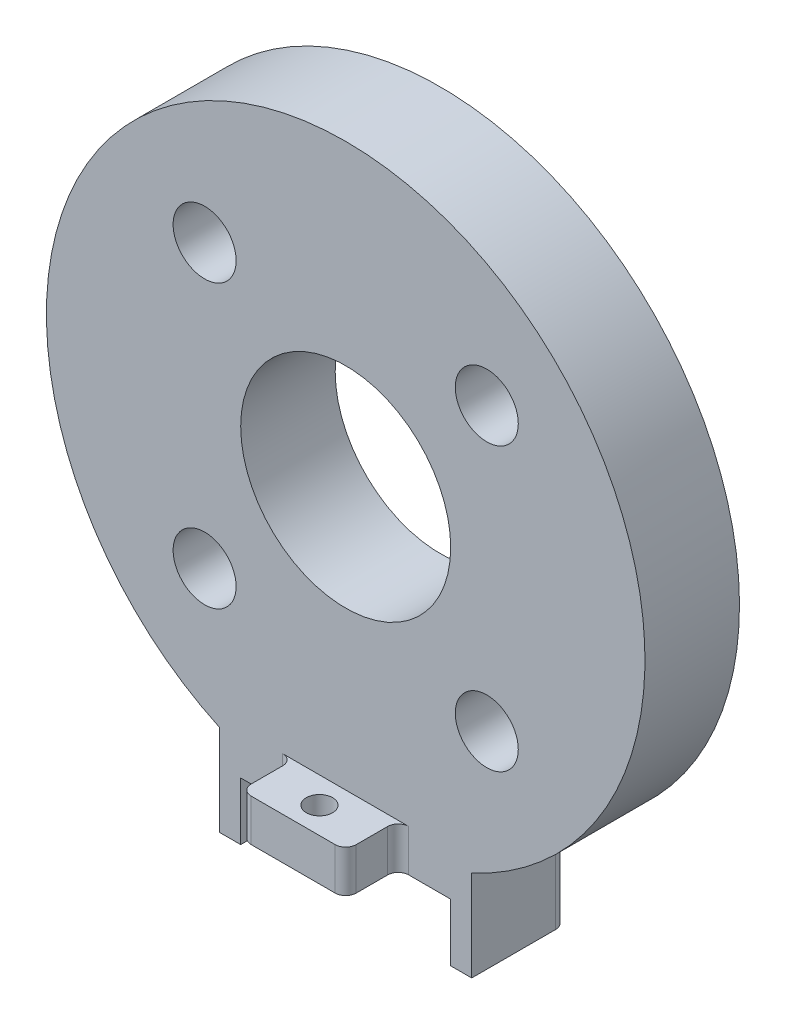
SolidWorks part; units mm, degrees
ref_plane "前视基准面" through (0, 0, 0) normal (0, 0, 1) x (1, 0, 0)
ref_plane "上视基准面" through (0, 0, 0) normal (0, 1, 0) x (1, 0, 0)
ref_plane "右视基准面" through (0, 0, 0) normal (1, 0, 0) x (0, 0, -1)
ref_plane "基准面1" through (0, 0, 0) normal (0, 0, -1) x (-1, 0, 0)
sketch "草图1" plane through (0, 0, 0) normal (0, 0, -1) x (-1, 0, 0)
  line L0 (-12, -25.8505) -> (-12, -34.5)
  line L1 (-12, -34.5) -> (12, -34.5)
  line L2 (12, -34.5) -> (12, -25.8505)
  arc A0 (12, -25.8505) -> (-12, -25.8505) centre (0, 0) ccw
extrude "凸台-拉伸1" add sketch "草图1" against normal blind 9
sketch "草图2" plane through (0, -34.5, 0) normal (0, -1, 0) x (1, 0, 0)
  line L0 (-10, 9) -> (-10, 1)
  line L1 (-10, 1) -> (10, 1)
  line L2 (10, 1) -> (10, 9)
  line L3 (10, 9) -> (-10, 9)
extrude "切除-拉伸1" cut sketch "草图2" against normal blind 5.5
sketch "草图3" plane through (0, 0, 9) normal (0, 0, 1) x (1, 0, 0)
  line L0 (5, -29) -> (-5, -29)
  line L1 (-5, -29) -> (-5, -25)
  line L2 (-5, -25) -> (5, -25)
  line L3 (5, -25) -> (5, -29)
extrude "凸台-拉伸2" add sketch "草图3" along normal blind 5
hole_wizard "Ø20.0 (20) 直径孔1" positions "草图5" profile "草图4" hole size "Ø20.0" standard "ANSI Metric"
sketch "草图5" plane through (0, 0, 0) normal (0, 0, -1) x (-1, 0, 0)
  point P0 (0, 0)
sketch "草图4" plane through (0, 0, 0) normal (1, 0, 0) x (0, 1, 0)
  line L0 (0, 0) -> (0, 14)
  line L1 (0, 14) -> (10, 14)
  line L2 (10, 14) -> (10, 0)
  line L5 (10, 0) -> (0, 0)
  line L11 (0, -6.35) -> (0, 107.95) construction
  dimension "通孔孔直径" = 20
  dimension "通孔孔深度" = 14
hole_wizard "Ø2.5 (2.5) 直径孔1" positions "草图7" profile "草图6" hole size "Ø2.5" standard "ANSI Metric"
sketch "草图7" plane through (0, -29, 0) normal (0, -1, 0) x (1, 0, 0)
  line L0 (-5, 14) -> (5, 14) construction
  point P0 (0, 11.5)
  point P1 (6.1393, 4.5265)
  point P2 (0, 11.5383)
  dimension "D1" = 2.5
sketch "草图6" plane through (0, -29, 11.5) normal (1, 0, 0) x (0, 0, -1)
  line L0 (0, 0) -> (0, 57.5)
  line L1 (0, 57.5) -> (1.25, 57.5)
  line L2 (1.25, 57.5) -> (1.25, 0)
  line L5 (1.25, 0) -> (0, 0)
  line L11 (0, -6.35) -> (0, 107.95) construction
  dimension "通孔孔直径" = 2.5
  dimension "通孔孔深度" = 57.5
hole_wizard "Ø2.5 (2.5) 直径孔2" positions "草图9" profile "草图8" hole size "Ø2.5" standard "ANSI Metric"
sketch "草图9" plane through (0, -29, 0) normal (0, -1, 0) x (1, 0, 0)
  line L0 (0, 0) -> (0, 24.1613) construction
  line L3 (-5, 9) -> (-10, 9) construction
  point P0 (5.5, 5)
  point P1 (-5.5, 5)
  point P11 (0, 0)
  dimension "D1" = 11
  dimension "D2" = 4
sketch "草图8" plane through (5.5, -29, 5) normal (1, 0, 0) x (0, 0, -1)
  line L0 (0, 0) -> (0, 4)
  line L1 (0, 4) -> (1.25, 4)
  line L2 (1.25, 4) -> (1.25, 0)
  line L5 (1.25, 0) -> (0, 0)
  line L10 (0, 4) -> (-1.25, 4) construction
  line L11 (0, -6.35) -> (0, 107.95) construction
  dimension "孔直径" = 2.5
  dimension "孔深度" = 4
  dimension "导头角度" = 180
hole_wizard "M3 六角头机械螺钉的柱形沉头孔1" positions "草图11" profile "草图10" counterbore size "M3" standard "ANSI Metric"
sketch "草图11" plane through (0, 0, 9) normal (0, 0, 1) x (1, 0, 0)
  point P0 (-13.435, -13.435)
  point P1 (-13.435, 13.435)
  point P2 (13.435, 13.435)
  point P3 (13.435, -13.435)
sketch "草图10" plane through (-13.435, -13.435, 9) normal (1, 0, 0) x (0, -1, 0)
  line L0 (0, 0) -> (0, 9)
  line L1 (0, 9) -> (1.6, 9)
  line L3 (1.6, 9) -> (1.6, 5)
  line L4 (1.6, 5) -> (3, 5)
  line L5 (3, 5) -> (3, 0)
  line L7 (3, 0) -> (0, 0)
  line L11 (0, -6.35) -> (0, 107.95) construction
  dimension "通孔孔直径" = 3.2
  dimension "通孔孔深度" = 9
  dimension "柱形沉头孔直径" = 6
  dimension "柱形沉头孔深度" = 5
fillet "圆角1" radius 0.5 2 edges at (10, -31.75, 1) (-10, -31.75, 1)
fillet "圆角2" radius 1 6 edges at (5, -27, 14) (-5, -27, 9) (5, -27, 9) (-12, -30.1753, 0) (-5, -27, 14) (12, -30.1753, 0)
